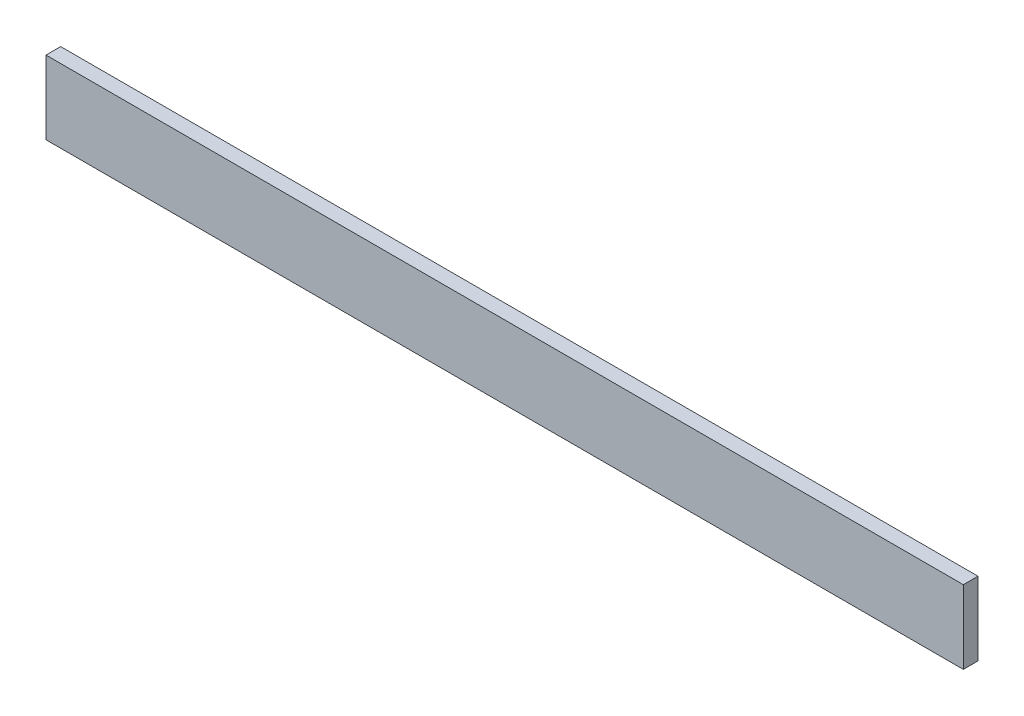
SolidWorks part; units mm, degrees
ref_plane "Plan de face" through (0, 0, 0) normal (0, 0, 1) x (1, 0, 0)
ref_plane "Plan de dessus" through (0, 0, 0) normal (0, 1, 0) x (1, 0, 0)
ref_plane "Plan de droite" through (0, 0, 0) normal (1, 0, 0) x (0, 0, -1)
sketch "Esquisse1" plane through (0, 0, 0) normal (0, 0, 1) x (1, 0, 0)
  line L1 (0, 0) -> (500, 0)
  line L2 (0, 0) -> (0, 40)
  line L3 (0, 40) -> (500, 40)
  line L4 (500, 0) -> (500, 40)
  dimension "D1" = 40
  dimension "D2" = 500
extrude "Boss.-Extru.1" add sketch "Esquisse1" along normal blind 8
